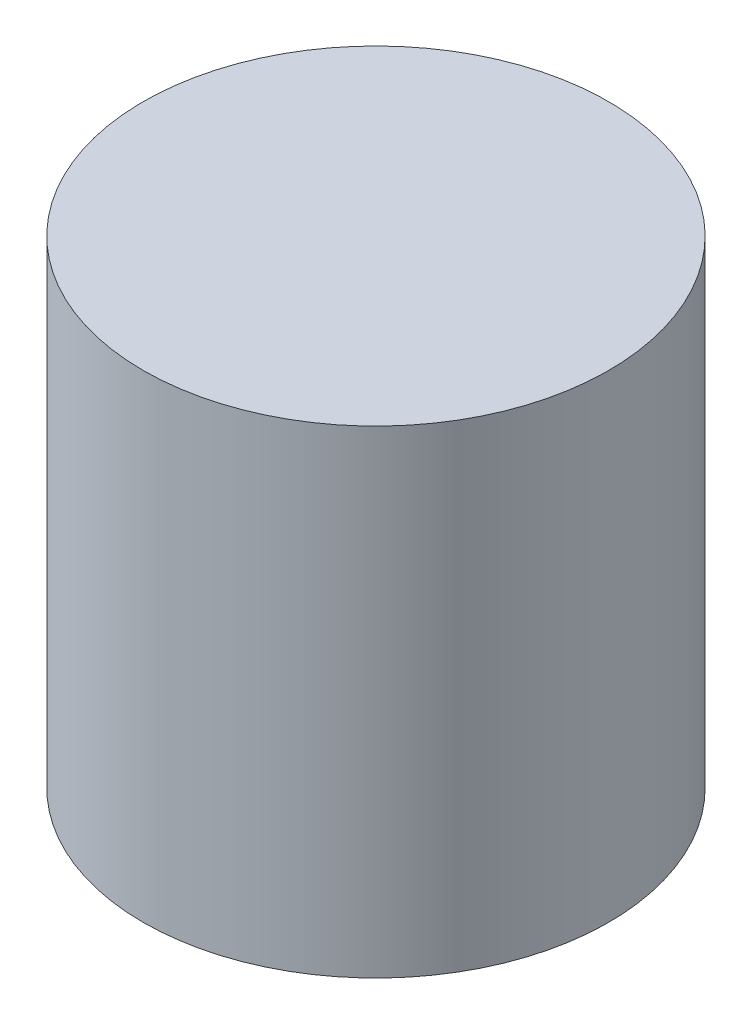
SolidWorks part; units mm, degrees
ref_plane "Front Plane" through (0, 0, 0) normal (0, 0, 1) x (1, 0, 0)
ref_plane "Top Plane" through (0, 0, 0) normal (0, 1, 0) x (1, 0, 0)
ref_plane "Right Plane" through (0, 0, 0) normal (1, 0, 0) x (0, 0, -1)
sketch "Sketch1" plane through (0, 0, 0) normal (0, 1, 0) x (1, 0, 0)
  circle A0 centre (0, 0) radius 284.48
extrude "Boss-Extrude1" add sketch "Sketch1" along normal blind 584.2
sketch "Sketch2" plane through (0, 0, 0) normal (0, -1, 0) x (-1, 0, 0)
  circle A0 centre (0, 0) radius 279.4
extrude "Cut-Extrude1" cut sketch "Sketch2" against normal blind 558.8
